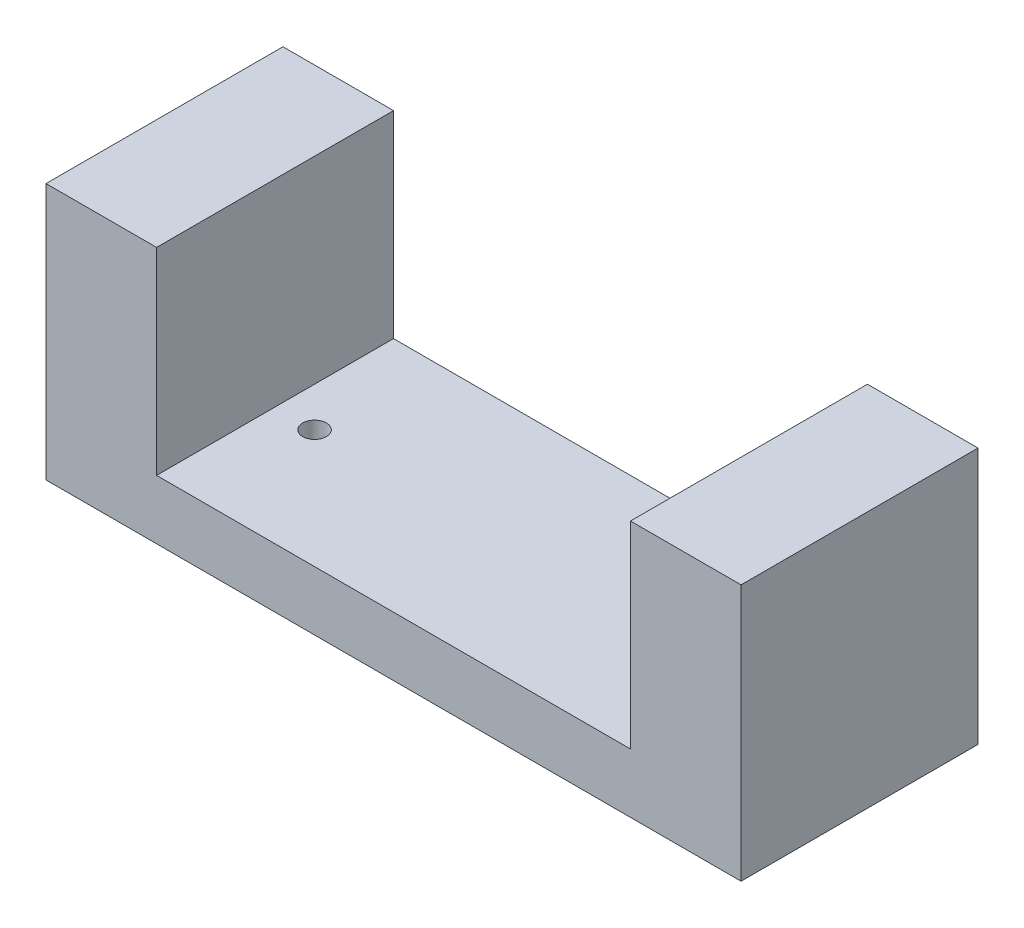
SolidWorks part; units mm, degrees
ref_plane "前视基准面" through (0, 0, 0) normal (0, 0, 1) x (1, 0, 0)
ref_plane "上视基准面" through (0, 0, 0) normal (0, 1, 0) x (1, 0, 0)
ref_plane "右视基准面" through (0, 0, 0) normal (1, 0, 0) x (0, 0, -1)
sketch "草图1" plane through (0, 0, 0) normal (0, 1, 0) x (1, 0, 0)
  line L1 (-44, -15) -> (44, -15)
  line L2 (-44, -15) -> (-44, 15)
  line L3 (-44, 15) -> (44, 15)
  line L4 (44, -15) -> (44, 15)
  line L5 (-44, -15) -> (44, 15) construction
  line L6 (-44, 15) -> (44, -15) construction
  point P0 (0, 0)
  dimension "D1" = 88
  dimension "D2" = 30
extrude "凸台-拉伸1" add sketch "草图1" along normal blind 32.5
sketch "草图2" plane through (0, 32.5, 0) normal (0, 1, 0) x (1, 0, 0)
  line L0 (-44, 0) -> (44, 0) construction
  line L1 (-44, 15) -> (-44, -15) construction
  line L2 (44, -15) -> (44, 15) construction
  line L3 (0, 15) -> (0, -15) construction
  line L4 (44, 15) -> (-44, 15) construction
  line L5 (-44, -15) -> (44, -15) construction
  circle A0 centre (-25, 0) radius 1.5
  circle A1 centre (25, 0) radius 1.5
  dimension "D1" = 3
  dimension "D2" = 50
extrude "切除-拉伸1" cut sketch "草图2" against normal through all
sketch "草图3" plane through (0, 32.5, 0) normal (0, 1, 0) x (1, 0, 0)
  line L0 (44, 15) -> (-44, 15) construction
  line L1 (-30, -15) -> (30, -15)
  line L2 (-30, -15) -> (-30, 15)
  line L3 (-30, 15) -> (30, 15)
  line L4 (30, -15) -> (30, 15)
  line L5 (-30, -15) -> (30, 15) construction
  line L6 (-30, 15) -> (30, -15) construction
  point P0 (0, 0)
  dimension "D1" = 60
extrude "切除-拉伸2" cut sketch "草图3" against normal blind 25
